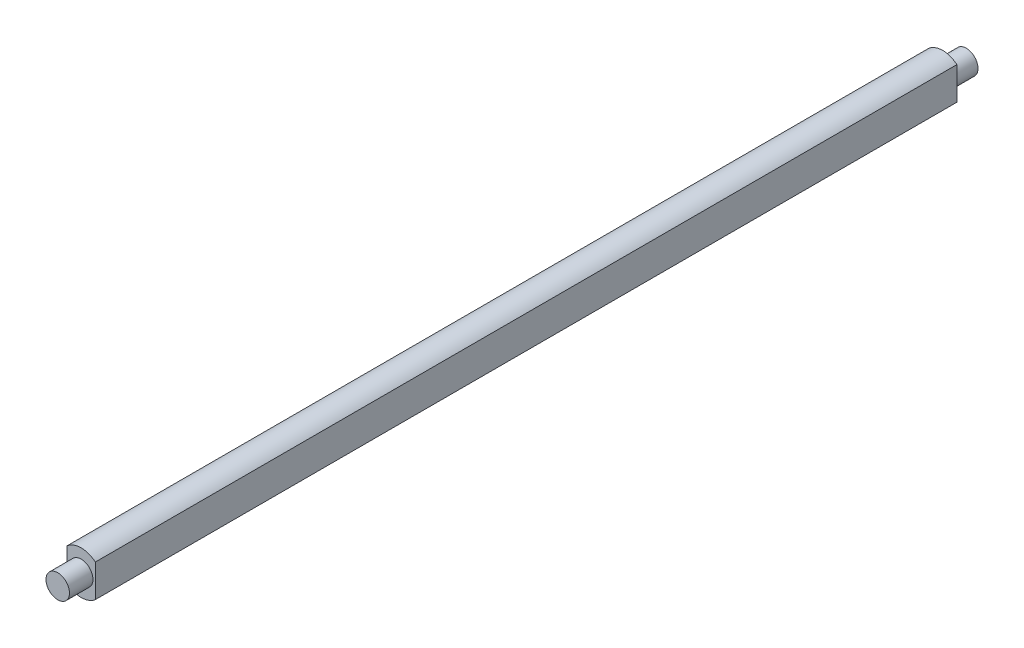
SolidWorks part; units mm, degrees
ref_plane "Front Plane" through (0, 0, 0) normal (0, 0, 1) x (1, 0, 0)
ref_plane "Top Plane" through (0, 0, 0) normal (0, 1, 0) x (1, 0, 0)
ref_plane "Right Plane" through (0, 0, 0) normal (1, 0, 0) x (0, 0, -1)
sketch "Çizim2" plane through (0, 0, 0) normal (0, 0, 1) x (1, 0, 0)
  line L0 (-1.7989, 2.08) -> (-1.7989, -2.08)
  line L1 (1.7989, 2.08) -> (1.7989, -2.08)
  circle A0 centre (0, 0) radius 2.75
  dimension "D1" = 5.5
  dimension "D2" = 4.16
  dimension "D3" = 4.16
extrude "Yükseklik-Ekstrüzyon1" add sketch "Çizim2" along normal blind 110 contours L1 A0 L0
sketch "Çizim5" plane through (0, 0, 110) normal (0, 0, 1) x (1, 0, 0)
  circle A0 centre (0, 0) radius 1.5
  dimension "D1" = 3
extrude "Yükseklik-Ekstrüzyon3" add sketch "Çizim5" along normal blind 3
sketch "Çizim6" plane through (0, 0, 0) normal (0, 0, -1) x (-1, 0, 0)
  circle A0 centre (0, 0) radius 1.5
  dimension "D1" = 3
extrude "Yükseklik-Ekstrüzyon4" add sketch "Çizim6" along normal blind 3
